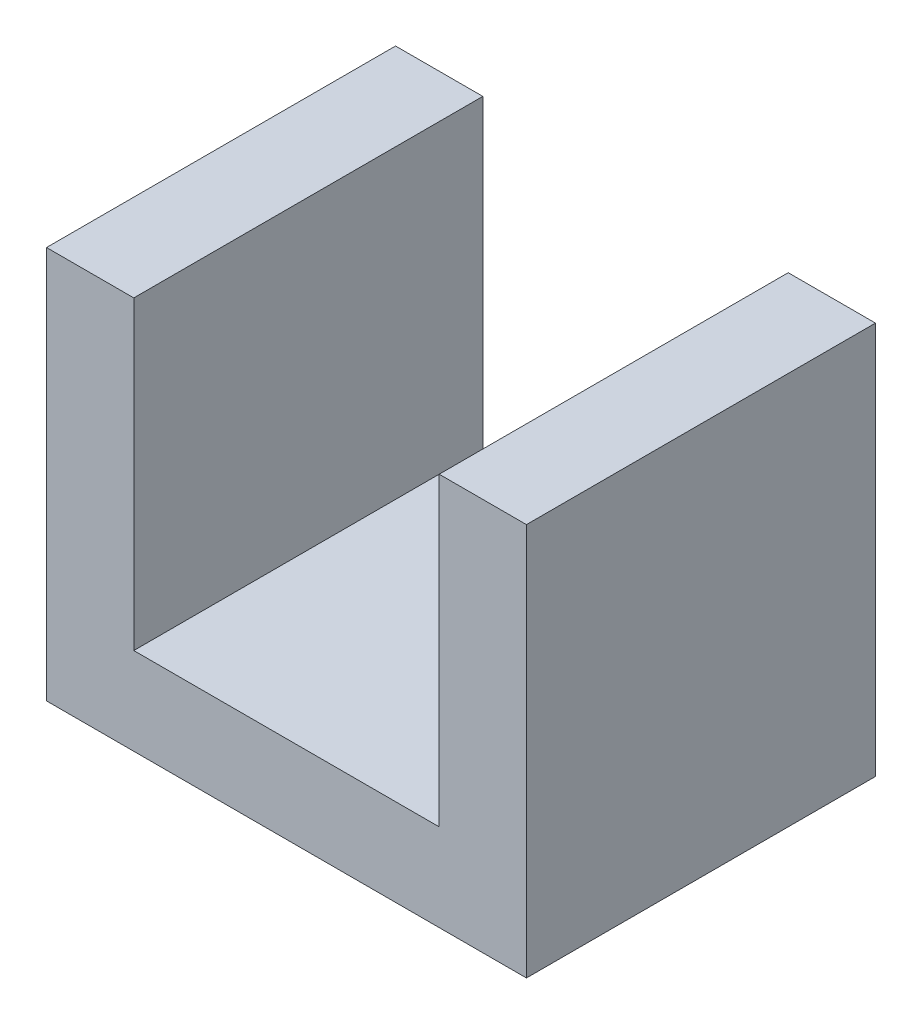
SolidWorks part; units mm, degrees
ref_plane "Front Plane" through (0, 0, 0) normal (0, 0, 1) x (1, 0, 0)
ref_plane "Top Plane" through (0, 0, 0) normal (0, 1, 0) x (1, 0, 0)
ref_plane "Right Plane" through (0, 0, 0) normal (1, 0, 0) x (0, 0, -1)
sketch "Sketch1" plane through (0, 0, 0) normal (0, 0, 1) x (1, 0, 0)
  line L0 (0, 7) -> (0, 0)
  line L1 (0, 0) -> (7, 0)
  line L2 (7, 0) -> (7, 7)
  line L3 (7, 7) -> (9, 7)
  line L4 (9, 7) -> (9, -2)
  line L5 (9, -2) -> (-2, -2)
  line L6 (-2, -2) -> (-2, 7)
  line L7 (-2, 7) -> (0, 7)
  dimension "D1" = 7
  dimension "D2" = 2
  dimension "D3" = 2
  dimension "D4" = 2
  dimension "D5" = 7
  dimension "D6" = 7
extrude "Boss-Extrude1" add sketch "Sketch1" along normal blind 8
